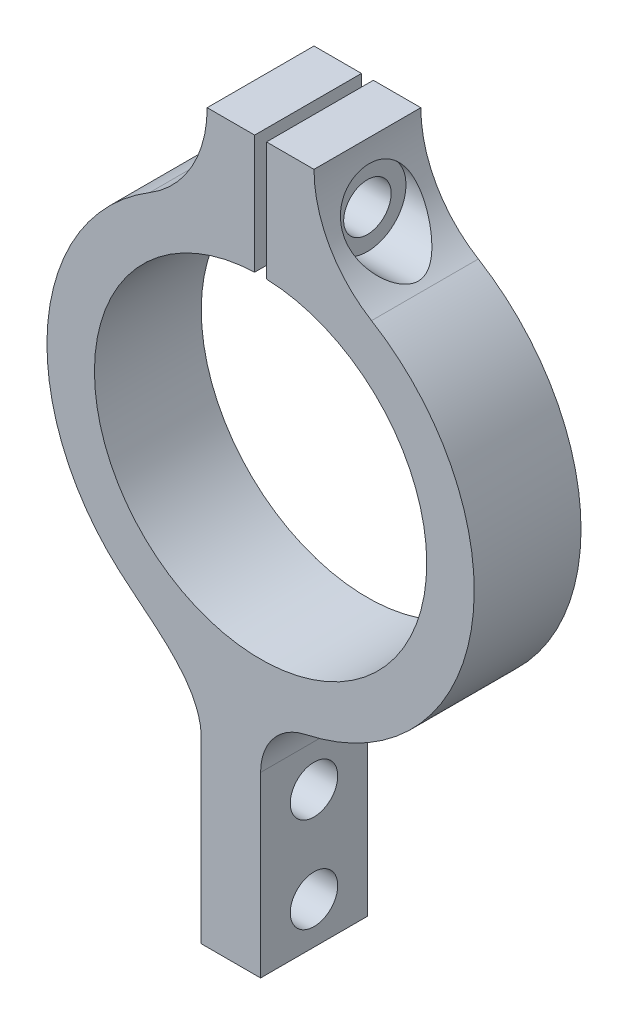
SolidWorks part; units mm, degrees
ref_plane "Front Plane" through (0, 0, 0) normal (0, 0, 1) x (1, 0, 0)
ref_plane "Top Plane" through (0, 0, 0) normal (0, 1, 0) x (1, 0, 0)
ref_plane "Right Plane" through (0, 0, 0) normal (1, 0, 0) x (0, 0, -1)
sketch "Sketch1" plane through (0, 0, 0) normal (0, 0, 1) x (1, 0, 0)
  line L0 (0, 0) -> (0, 36) construction
  line L1 (0, -44.5174) -> (0, -74.5174)
  line L2 (0, -74.5174) -> (-10, -74.5174)
  line L3 (-10, -74.5174) -> (-10, -44.5174)
  line L6 (0, 36) -> (0, 48) construction
  line L7 (0, 48) -> (1, 48) construction
  line L8 (1, 48) -> (1, 27.9821)
  line L9 (1, 48) -> (9, 48)
  line L11 (0, 48) -> (-1, 48) construction
  line L12 (-1, 48) -> (-1, 27.9821)
  line L13 (-1, 48) -> (-9, 48)
  arc A0 (-1, 27.9821) -> (1, 27.9821) centre (0, 0) ccw
  arc A1 (0, -44.5174) -> (7.5321, -35.2032) centre (9.525, -44.5174) cw
  arc A2 (0, 36) -> (-1, 35.9861) centre (0, 0) ccw construction
  arc A3 (9, 48) -> (18.6944, 30.7656) centre (29.1667, 48) ccw
  arc A4 (-18.6944, 30.7656) -> (-23.8817, -26.9382) centre (0, 0) ccw
  arc A6 (-18.6944, 30.7656) -> (-9, 48) centre (-29.1667, 48) ccw
  arc A8 (7.5321, -35.2032) -> (18.6944, 30.7656) centre (0, 0) ccw
  spline S0 degree 3 poles (-23.8817, -26.9382) (-18.2947, -31.8913) (-10, -36.821) (-10, -44.5174) knots 0 0 0 0 1 1 1 1
  point P27 (0, -36)
  dimension "D1" = 56
  dimension "D3" = 30
  dimension "D4" = 10
  dimension "D2" = 36
  dimension "D11" = 9.525
  dimension "D6" = 12
  dimension "D7" = 1
  dimension "D8" = 8
  dimension "D9" = 1
  dimension "D10" = 8
extrude "Boss-Extrude1" add sketch "Sketch1" along normal blind 18
sketch "Sketch7" plane through (1, 0, 0) normal (-1, 0, 0) x (0, 0, 1)
  line L0 (9, 27.9821) -> (9, 48) construction
  line L1 (18, 27.9821) -> (0, 27.9821) construction
  line L2 (18, 48) -> (0, 48) construction
  circle A0 centre (9, 37.9911) radius 4
  dimension "D1" = 8
extrude "Cut-Extrude4" cut sketch "Sketch7" against normal through all and the other way through all
ref_plane "Plane2" through (-9, 0, 0) normal (1, 0, 0) x (0, 0, -1)
sketch "Sketch8" plane through (-9, 0, 0) normal (1, 0, 0) x (0, 0, -1)
  circle A0 centre (-9, 37.9911) radius 6.5
  dimension "D1" = 13
extrude "Cut-Extrude5" cut sketch "Sketch8" against normal blind 18
ref_plane "Plane3" through (9, 0, 0) normal (-1, 0, 0) x (0, 0, 1)
sketch "Sketch10" plane through (9, 0, 0) normal (-1, 0, 0) x (0, 0, 1)
  circle A0 centre (9, 37.9911) radius 6.5
  dimension "D1" = 13
extrude "Cut-Extrude6" cut sketch "Sketch10" against normal blind 18
sketch "Sketch12" plane through (0, 0, 0) normal (1, 0, 0) x (0, 0, -1)
  line L0 (-9, -74.5174) -> (-9, -44.5174) construction
  line L2 (-18, -44.5174) -> (0, -44.5174) construction
  line L3 (-18, -74.5174) -> (0, -74.5174) construction
  circle A0 centre (-9, -51.5174) radius 4
  circle A1 centre (-9, -51.5174) radius 7 construction
  circle A2 centre (-9, -67.5174) radius 4
  circle A3 centre (-9, -67.5174) radius 7 construction
  point P2 (-9, -90.2898)
  point P3 (-9, -74.5174)
  point P12 (-9, -68.5135)
  point P15 (0, 0)
  dimension "D1" = 8
  dimension "D2" = 14
  dimension "D3" = 14
  dimension "D4" = 8
extrude "Cut-Extrude7" cut sketch "Sketch12" against normal through all
